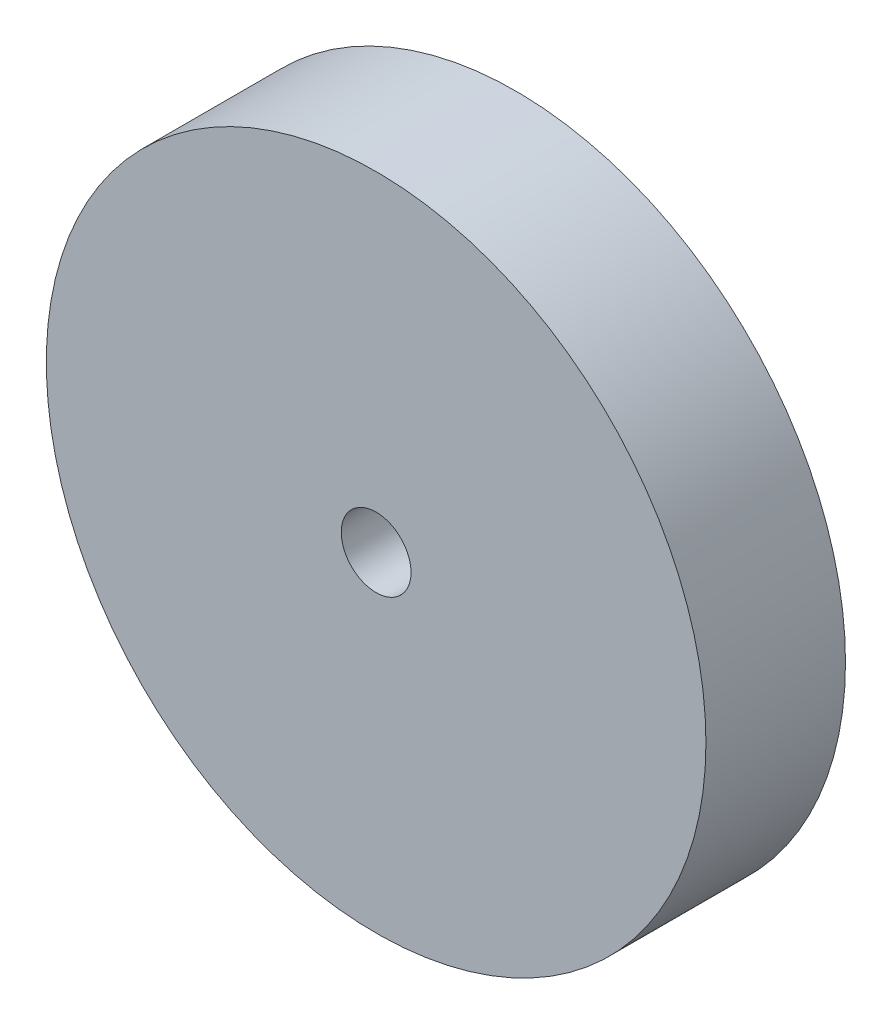
SolidWorks part; units mm, degrees
ref_plane "Front Plane" through (0, 0, 0) normal (0, 0, 1) x (1, 0, 0)
ref_plane "Top Plane" through (0, 0, 0) normal (0, 1, 0) x (1, 0, 0)
ref_plane "Right Plane" through (0, 0, 0) normal (1, 0, 0) x (0, 0, -1)
sketch "Sketch1" plane through (0, 0, 0) normal (0, 0, 1) x (1, 0, 0)
  circle A0 centre (0, 0) radius 9.453
  dimension "D1" = 18.906
extrude "Boss-Extrude1" add sketch "Sketch1" along normal blind 4
sketch "Sketch2" plane through (0, 0, 4) normal (0, 0, 1) x (1, 0, 0)
  circle A0 centre (0, 0) radius 1
  dimension "D1" = 2
extrude "Cut-Extrude1" cut sketch "Sketch2" against normal through all
